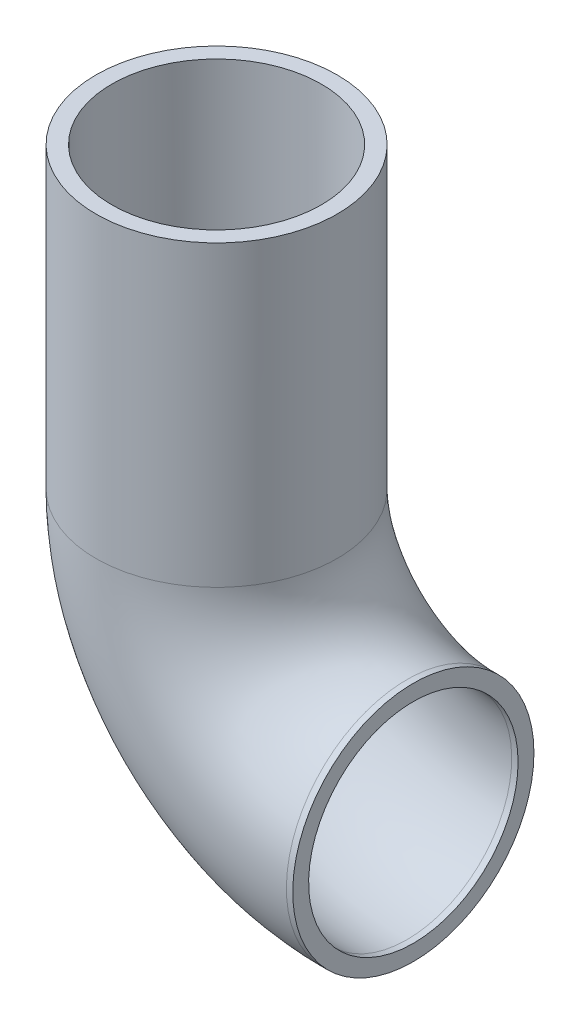
SolidWorks part; units mm, degrees
ref_plane "Front Plane" through (0, 0, 0) normal (0, 0, 1) x (1, 0, 0)
ref_plane "Top Plane" through (0, 0, 0) normal (0, 1, 0) x (1, 0, 0)
ref_plane "Right Plane" through (0, 0, 0) normal (1, 0, 0) x (0, 0, -1)
sketch "Sketch1" plane through (0, 0, 0) normal (0, 0, 1) x (1, 0, 0)
  line L0 (0, 0) -> (-1, 0)
  line L1 (-31, 30) -> (-31, 77)
  arc A0 (-1, 0) -> (-31, 30) centre (-1, 30) cw
  dimension "D1" = 30
  dimension "D2" = 1
  dimension "D3" = 47
sketch "Sketch2" plane through (0, 0, 0) normal (1, 0, 0) x (0, 0, -1)
  circle A0 centre (0, 0) radius 19
  dimension "D1" = 38
sweep "Sweep-Thin1" add profiles "Sketch2" path "Sketch1" parameters "D1"=2.5
